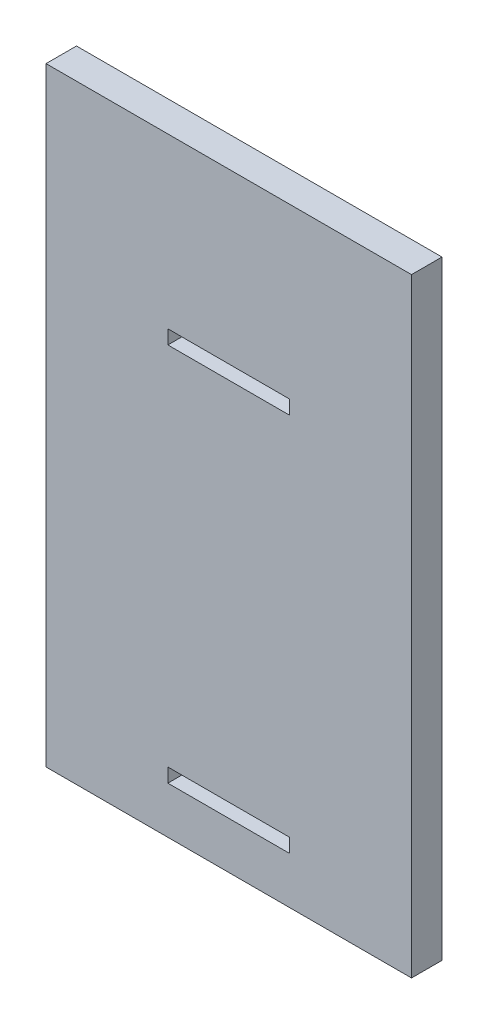
SolidWorks part; units mm, degrees
material "PBT General Purpose"
ref_plane "Front Plane" through (0, 0, 0) normal (0, 0, 1) x (1, 0, 0)
ref_plane "Top Plane" through (0, 0, 0) normal (0, 1, 0) x (1, 0, 0)
ref_plane "Right Plane" through (0, 0, 0) normal (1, 0, 0) x (0, 0, -1)
sketch "frame_outline" plane through (0, 0, 0) normal (0, 0, 1) x (1, 0, 0)
  line L124 (0, 0) -> (3, 0)
  line L125 (0, 0) -> (0, 5)
  line L126 (0, 5) -> (3, 5)
  line L127 (3, 0) -> (3, 5)
  line L128 (1, 3.615) -> (2, 3.615)
  line L129 (1, 3.615) -> (1, 3.5)
  line L130 (1, 3.5) -> (2, 3.5)
  line L131 (2, 3.615) -> (2, 3.5)
  line L132 (1, 0.5) -> (2, 0.5)
  line L133 (1, 0.5) -> (1, 0.385)
  line L134 (1, 0.385) -> (2, 0.385)
  line L135 (2, 0.5) -> (2, 0.385)
  point P12 (1.5, 0.385)
  point P13 (1.5, 0)
  dimension "D1" = 1
  dimension "D2" = 3
  dimension "D3" = 0.115
  dimension "D4" = 5
  dimension "D5" = 3
  dimension "D6" = 1.5
extrude "Boss-Extrude1" add sketch "frame_outline" along normal mid plane 0.25
equation "\"t\"= 0.25'thickness of the sheets"
equation "\"t_cf\"= 0.115'thickness of single carbon fiber layer"
equation "\"t_kapton\"= 0.025'thickness of single Kapton flex layer"
equation "\"t_fr4\"= 0.1'thickness of FR4 with copper layer"
equation "\"joint_flex\"= 0.1'Width of flextures gap"
equation "\"joint_flex_eff\"= 0.02'Width of flecture after castelation"
equation "\"joint_fold\"= 0.2'Width of folding joints for 90deg fold"
equation "\"gap_tolerance\"= 0.002'Width to have interfecence fit between carbon fiber inserts"
equation "\"assemble_angle\"= 90'Angle of assembly parts"
equation "\"D1@Boss-Extrude1\"=\"t\""
equation "\"link_lift\"= 0.5'Actuation linkage amplification for the lift motion"
equation "\"link_swing\"= 0.45'Actuation linkage amplification for the swing motion"
